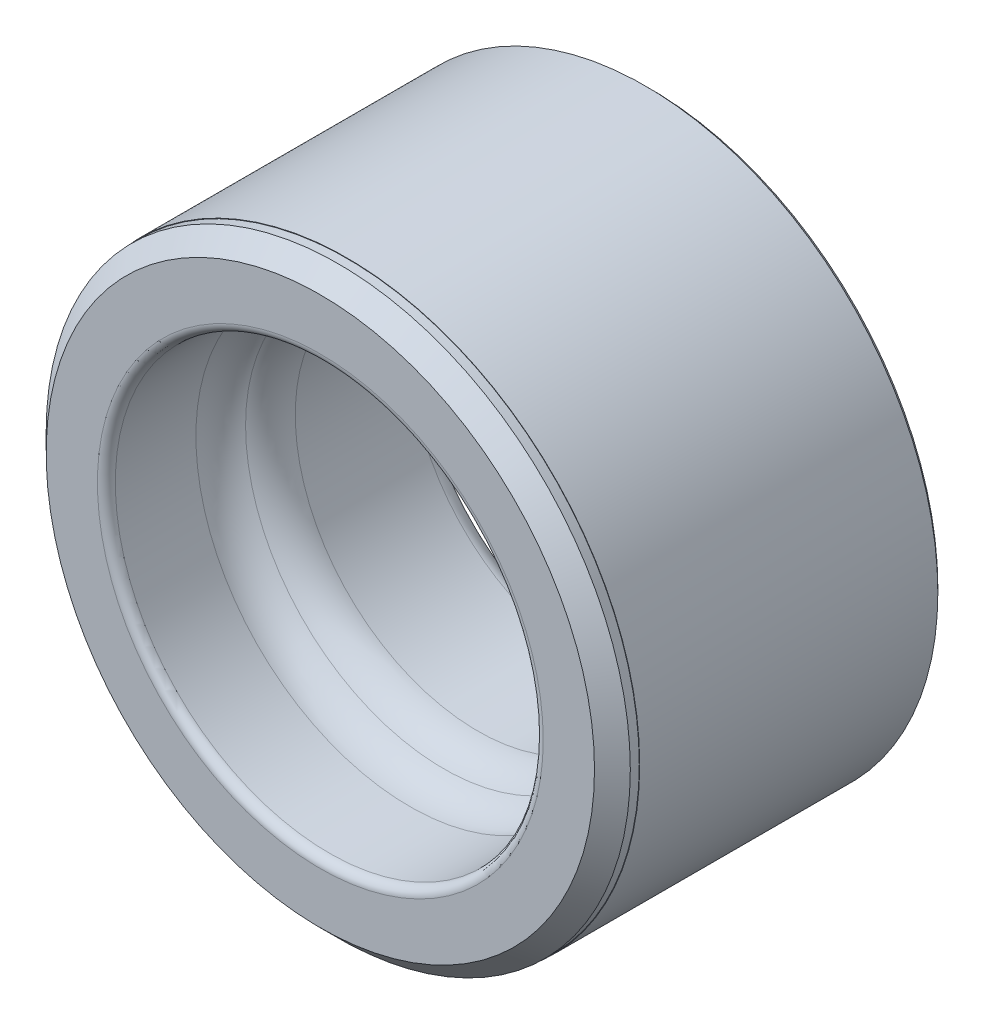
SolidWorks part; units mm, degrees
ref_plane "Front" through (0, 0, 0) normal (0, 0, 1) x (1, 0, 0)
ref_plane "Top" through (0, 0, 0) normal (0, 1, 0) x (1, 0, 0)
ref_plane "Right" through (0, 0, 0) normal (1, 0, 0) x (0, 0, -1)
sketch "Sketch1" plane through (0, 0, 0) normal (1, 0, 0) x (0, 0, -1)
  line L0 (0, 0) -> (36.8, 0) construction
  line L1 (2, 32.625) -> (3, 32.625)
  line L2 (3, 32.675) -> (36.3, 32.675)
  line L3 (0, 24.9) -> (0, 30.625)
  line L4 (3, 32.625) -> (3, 32.675)
  line L5 (17.5993, 20.4) -> (30.3914, 20.4)
  line L6 (0, 32.675) -> (36.8, 32.675) construction
  line L7 (0, 32.625) -> (36.8, 32.625) construction
  line L8 (3, 0) -> (3, 32.675) construction
  line L9 (0, 0) -> (0, 32.675) construction
  line L10 (36.8, 29.5) -> (36.8, 32.175)
  line L11 (36.8, 29.5) -> (32.1235, 21.4)
  line L12 (1, 23.9) -> (10, 23.9)
  line L13 (0, 20.4) -> (36.8, 20.4) construction
  line L14 (0, 30.625) -> (2, 32.625)
  line L15 (36.3, 32.675) -> (36.8, 32.175)
  line L18 (0, 23.9) -> (36.8, 23.9) construction
  arc A0 (30.3914, 20.4) -> (32.1235, 21.4) centre (30.3914, 22.4) ccw
  arc A1 (13.7997, 22.15) -> (10, 23.9) centre (10, 18.9) ccw
  arc A2 (13.7997, 22.15) -> (17.5993, 20.4) centre (17.5993, 25.4) ccw
  arc A3 (1, 23.9) -> (0, 24.9) centre (1, 24.9) cw
  point P18 (10, 0)
  point P19 (10, 32)
  dimension "D3" = 2
  dimension "D4" = 10
  dimension "D5" = 5
  dimension "D12" = 5
  dimension "D13" = 1
  dimension "D1" = 36.8
  dimension "D2" = 30
  dimension "D6" = 20.4
  dimension "D7" = 23.9
  dimension "D8" = 32.675
  dimension "D9" = 32.625
  dimension "D10" = 3
  dimension "D11" = 29.5
  dimension "D14" = 2
  dimension "D15" = 45
  dimension "D16" = 0.5
  dimension "D17" = 45
revolve "Revolve1" add sketch "Sketch1" angle 360 about L0
